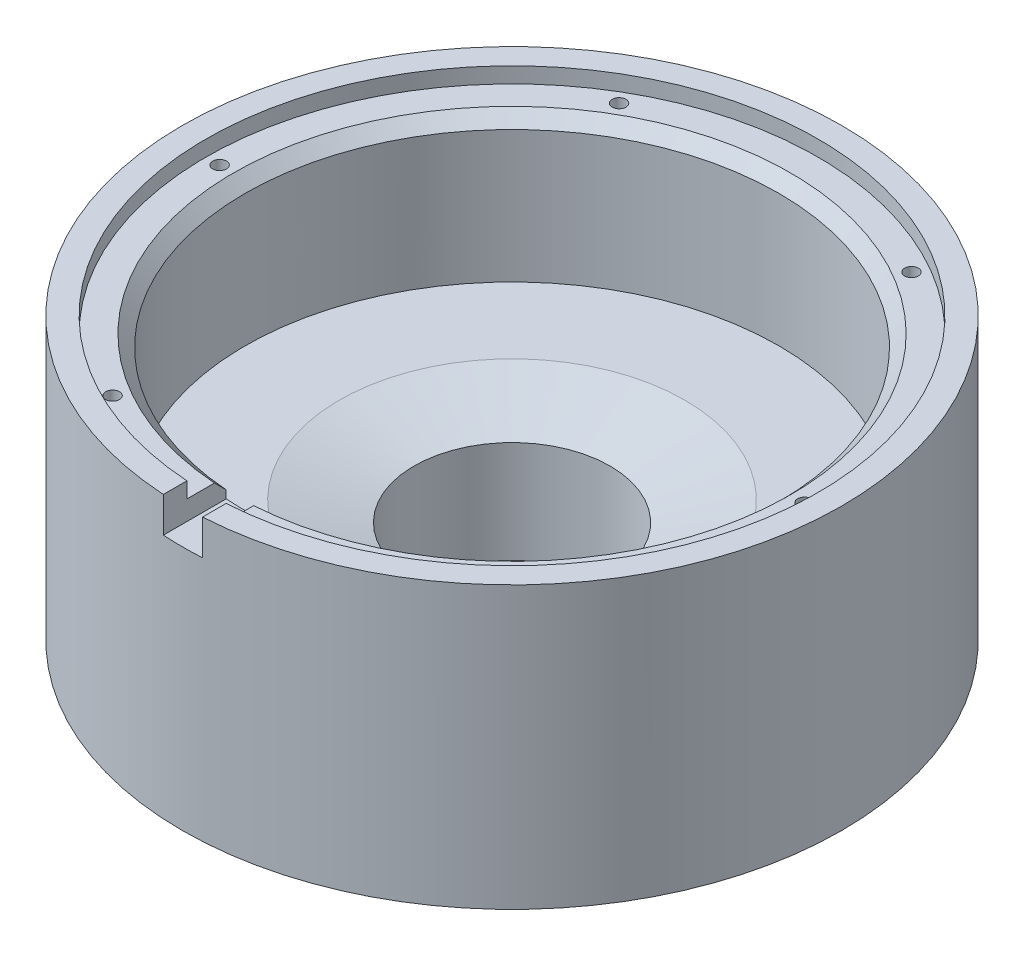
SolidWorks part; units mm, degrees
material "1060 Alloy"
ref_plane "Front Plane" through (0, 0, 0) normal (0, 0, 1) x (1, 0, 0)
ref_plane "Top Plane" through (0, 0, 0) normal (0, 1, 0) x (1, 0, 0)
ref_plane "Right Plane" through (0, 0, 0) normal (1, 0, 0) x (0, 0, -1)
sketch "Sketch7" plane through (0, 0, 0) normal (0, 0, 1) x (1, 0, 0)
  line L0 (0, -30.2319) -> (0, 30.2319) construction
  line L1 (-42.0375, 21.59) -> (-39.0375, 21.59)
  line L2 (-39.0375, 21.59) -> (-39.0375, 19.59)
  line L3 (-39.0375, 19.59) -> (-34.0375, 19.59)
  line L4 (-34.0375, 19.59) -> (-34.0375, 1.25)
  line L7 (-22.0375, 1.25) -> (-34.0375, 1.25)
  line L8 (-12.5, -1.25) -> (-12.5, -14.25)
  line L9 (-12.5, -14.25) -> (-42.0375, -14.25)
  line L10 (-42.0375, -14.25) -> (-42.0375, 21.59)
  line L11 (-17.2688, 0) -> (0, 0) construction
  line L12 (-22.0375, 1.25) -> (-12.5, -1.25)
  point P3 (0, 0)
  point P4 (0, 0)
  point P11 (-10.5839, 0)
  point P12 (0, 0)
  point P18 (0, 0)
  point P19 (-17.2688, 0)
  point P20 (-36.5375, 19.59)
  dimension "D1" = 3
  dimension "D2" = 2
  dimension "D3" = 5
  dimension "D4" = 34.0375
  dimension "D8" = 12
  dimension "D6" = 13
  dimension "D9" = 12.5
  dimension "D5" = 18.34
  dimension "D7" = 2.5
revolve "Base Motor Housing" add sketch "Sketch7" angle 360 about L0
sketch "Sketch8" plane through (0, 21.59, 0) normal (0, 1, 0) x (1, 0, 0)
  line L0 (0, 0) -> (0, -42.0375) construction
  line L1 (-2.5, -42.0375) -> (2.5, -42.0375)
  line L2 (-2.5, -42.0375) -> (-2.5, -33.9456)
  line L3 (-2.5, -33.9456) -> (2.5, -33.9456)
  line L4 (2.5, -42.0375) -> (2.5, -33.9456)
  circle A0 centre (0, 0) radius 42.0375 construction
  circle A1 centre (0, 0) radius 34.0375 construction
  point P10 (0, -42.0375)
  dimension "D1" = 5
extrude "Wire Hole" cut sketch "Sketch8" against normal offset from surface (4.5 mm away) 2.5 up to face at (0, 19.59, -39.0375)
chamfer "Chamfer1" distance 1.5 angle 45 1 edges at (0, 19.59, -34.0375)
sketch "Sketch9" plane through (0, 19.59, 0) normal (0, 1, 0) x (1, 0, 0)
  line L0 (-35.5375, 0) -> (-39.0375, 0) construction
  line L2 (-2.5, -35.4495) -> (-2.5, -33.9456)
  line L3 (2.5, -33.9456) -> (2.5, -35.4495)
  circle A0 centre (0, 0) radius 34.0375 construction
  circle A1 centre (0, 0) radius 34.0375 construction
  circle A2 centre (0, 0) radius 37.2875 construction
  circle A3 centre (-37.2875, 0) radius 0.875
  circle A4 centre (-18.6438, 32.2919) radius 0.875
  circle A5 centre (18.6437, 32.2919) radius 0.875
  circle A6 centre (37.2875, 0) radius 0.875
  circle A7 centre (18.6438, -32.2919) radius 0.875
  circle A8 centre (-18.6437, -32.2919) radius 0.875
  arc A9 (2.5, -38.9574) -> (-2.5, -38.9574) centre (0, 0) ccw construction
  arc A10 (2.5, -38.9574) -> (-2.5, -38.9574) centre (0, 0) ccw construction
  arc A11 (2.5, -33.9456) -> (-2.5, -33.9456) centre (0, 0) ccw
  arc A12 (2.5, -35.4495) -> (-2.5, -35.4495) centre (0, 0) ccw
  arc A14 (2.5, -35.4495) -> (-2.5, -35.4495) centre (0, 0) ccw construction
  point P21 (0, 0)
  point P31 (-37.2875, 0)
  dimension "D2" = 1.75
  dimension "D3" = 6
extrude "Front-Holes" cut sketch "Sketch9" against normal blind 6
sketch "Sketch10" plane through (0, -14.25, 0) normal (0, -1, 0) x (1, 0, 0)
  line L0 (-12.5, 0) -> (-42.0375, 0) construction
  circle A2 centre (0, 0) radius 42.0375 construction
  circle A3 centre (0, 0) radius 42.0375 construction
  circle A4 centre (-27.2687, 0) radius 2.875
  circle A5 centre (-13.6344, 23.6154) radius 2.875
  circle A6 centre (13.6344, 23.6154) radius 2.875
  circle A7 centre (27.2687, 0) radius 2.875
  circle A8 centre (13.6344, -23.6154) radius 2.875
  circle A9 centre (-13.6344, -23.6154) radius 2.875
  circle A10 centre (0, 0) radius 27.2687 construction
  circle A11 centre (0, 0) radius 12.5 construction
  circle A12 centre (0, 0) radius 12.5 construction
  point P12 (0, 0)
  point P22 (0, 0)
  point P24 (0, 0)
  point P25 (0, 0)
  dimension "D1" = 5.75
  dimension "D2" = 6
extrude "Back-Holes" cut sketch "Sketch10" against normal blind 8
equation "\"D2@Sketch9\"=\"Back_mount_hole\""
equation "\"Stator_OD\"= 68'No Tolerance given"
equation "\"D4@Sketch7\"= 1 / 2 * \"Stator_OD\" + \"Stator_Gap\""
equation "\"A\"=18.34 'taken off spec sheet for 06808 (A)"
equation "\"Rotor_ID\"= 34'No Tolerance Given"
equation "\"back_bearing_Thickness\"= 8'randomish, thinnest off mcmaster"
equation "\"D8@Sketch7\"=1/2*(\"Stator_OD\"-\"Rotor_ID\")-5"
equation "\"D6@Sketch7\"=\"back_bearing_Thickness\"+5"
equation "\"back_bearing_OD\"= 25'currently non-sense"
equation "\"D9@Sketch7\"=\"back_bearing_OD\"*1/2"
equation "\"D5@Sketch7\"=\"A\""
equation "\"Stator_Gap\"= 0.0375'+- 0.0125 (From 1.3.3.1 Kollmorgen manual)"
equation "\"Back_mount_hole\"= 1.75'To be tapped to M2 (USE LOCKTITE)"
equation "\"D1@Back-Holes\" = \"back_bearing_Thickness\""
equation "\"facePlate_Mount_Hole\"= 5.75'To be tapped to M6"
equation "\"D1@Sketch10\"=\"facePlate_Mount_Hole\""
equation "\"final_shaftD\"= 8'NEMA 23 shaft diameter. Should fit with harmonic?"
equation "\"back_bearing_ID\"= 15'Random number"
equation "\"final_shaftL\"= 50'random length. Idk"
equation "\"back_bearing_IDOD\"= 20'Random number, OD of the inner bearing ring"
equation "\"rotor_shaftD\"= \"Rotor_ID\" - (0.0185)*2'+-0.0065 (from manual)"
equation "\"front_bearing_ID\"= 12'random"
equation "\"front_bearing_OD\"= 20'random"
equation "\"front_bearing_IDOD\"= 14'random"
equation "\"front_bearing_Thickness\"= 5'randomish, thinnest off mcmaster"
equation "\"rotor_thickness\"= 2.4'measured off CAD"
equation "\"rotor_height\"= 14.76'+-0.08 taken off spec sheet for 06808 (C)"
